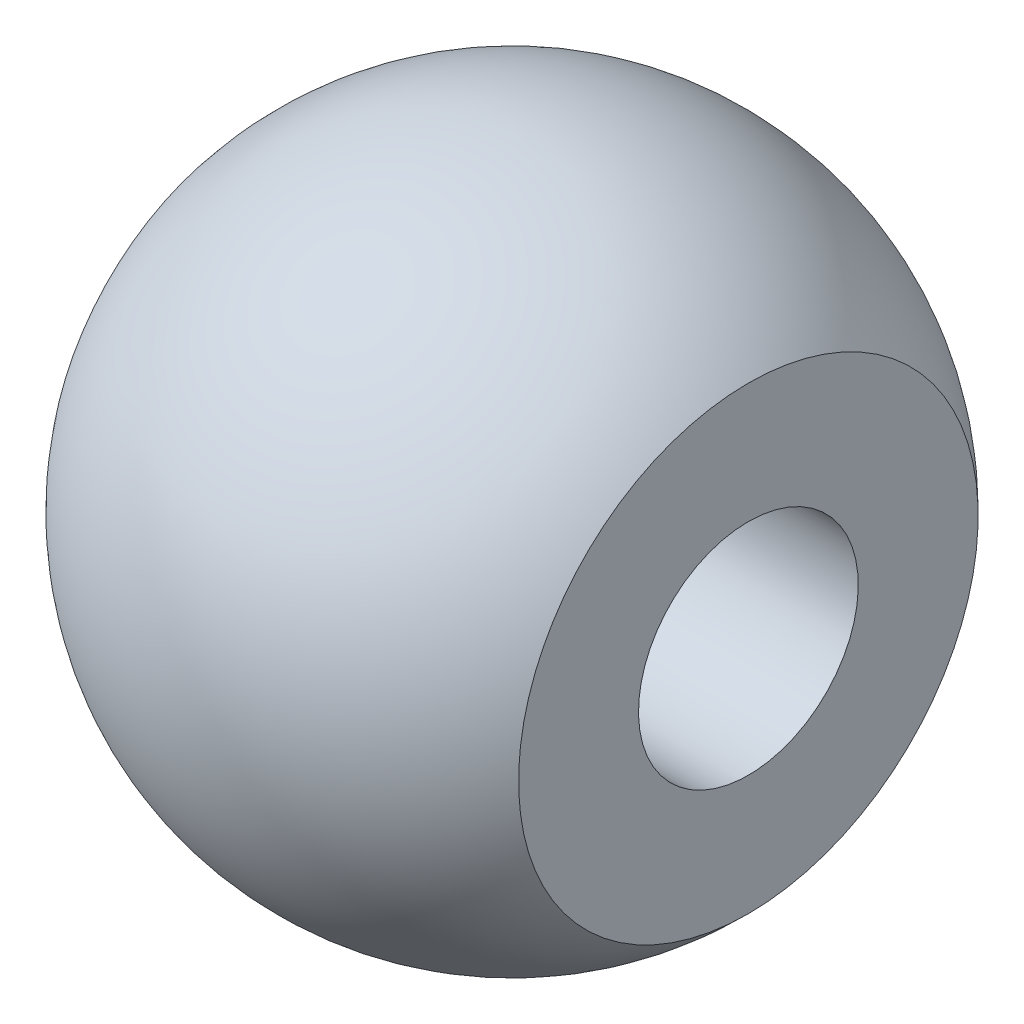
SolidWorks part; units mm, degrees
ref_plane "Front Plane" through (0, 0, 0) normal (0, 0, 1) x (1, 0, 0)
ref_plane "Top Plane" through (0, 0, 0) normal (0, 1, 0) x (1, 0, 0)
ref_plane "Right Plane" through (0, 0, 0) normal (1, 0, 0) x (0, 0, -1)
sketch "Sketch3" plane through (0, 0, 0) normal (0, 0, 1) x (1, 0, 0)
  line L0 (0, -2) -> (0, 2) construction
  line L5 (-4.6981, -7.2816) -> (-4.6981, 3.7236) construction
  line L6 (-3.6981, -2) -> (4.3019, -2)
  line L8 (-3.6981, -2) -> (-4.6981, -3.7321)
  line L9 (4.3019, 0) -> (-4.6981, 0) construction
  line L10 (4.3019, -2) -> (4.3019, -4.1825)
  line L11 (4.3019, -2) -> (4.3019, -4.1825)
  arc A1 (-4.6981, -3.7321) -> (4.3019, -4.1825) centre (0, 0) ccw
  point P10 (4.3019, 0)
  point P11 (0, 0)
  dimension "D4" = 60
  dimension "D1" = 4
  dimension "D3" = 6
  dimension "D2" = 2
  dimension "D6" = 8
  dimension "D7" = 1
revolve "Revolve2" add sketch "Sketch3" angle 360 about L9
